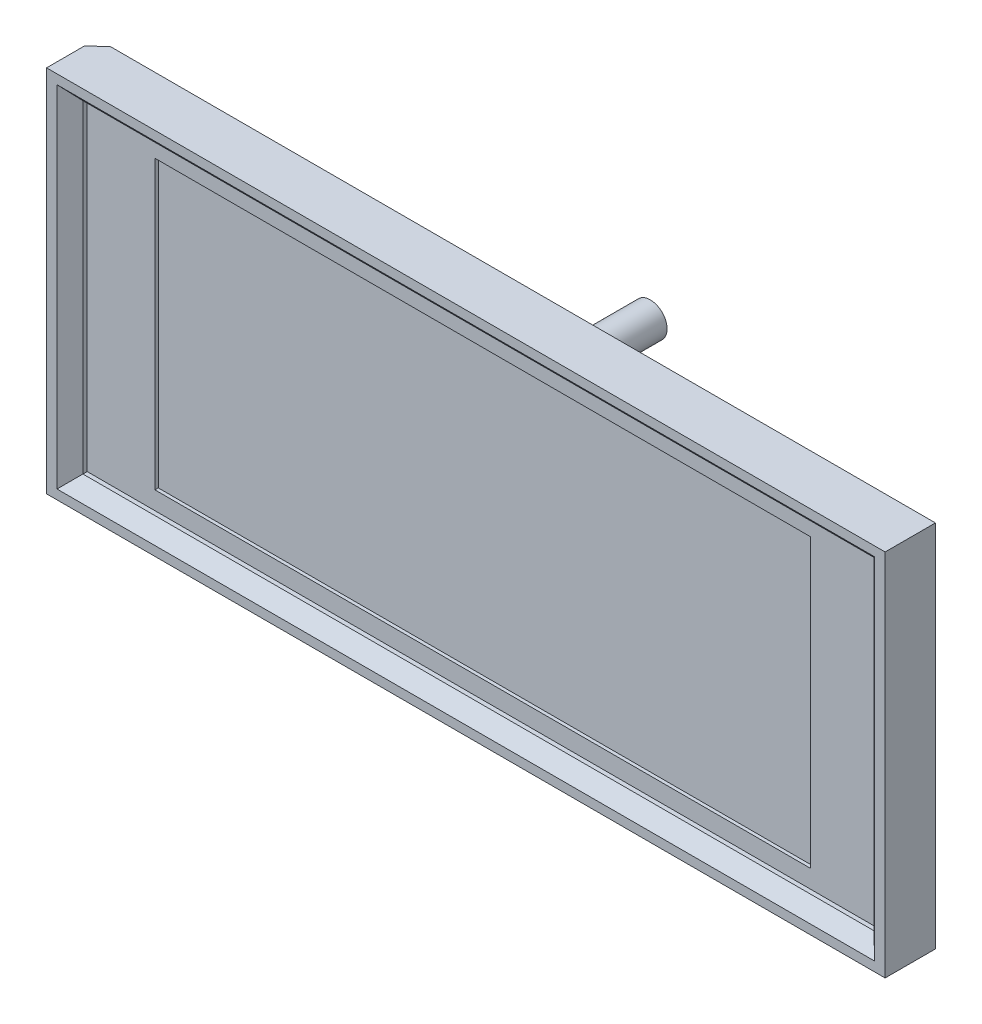
SolidWorks part; units mm, degrees
ref_plane "Front" through (0, 0, 0) normal (0, 0, 1) x (1, 0, 0)
ref_plane "Top" through (0, 0, 0) normal (0, 1, 0) x (1, 0, 0)
ref_plane "Right" through (0, 0, 0) normal (1, 0, 0) x (0, 0, -1)
sketch "草图2" plane through (0, 0, 0) normal (0, 0, 1) x (1, 0, 0)
  line L1 (-125, -55) -> (125, -55)
  line L2 (-125, -55) -> (-125, 55)
  line L3 (-125, 55) -> (125, 55)
  line L4 (125, -55) -> (125, 55)
  line L5 (-125, -55) -> (125, 55) construction
  line L6 (-125, 55) -> (125, -55) construction
  point P0 (0, 0)
extrude "凸台-拉伸1" add sketch "草图2" along normal blind 15
sketch "草图3" plane through (0, 0, 15) normal (0, 0, 1) x (1, 0, 0)
  line L1 (-117.8972, -48.1943) -> (117.8972, -48.1943)
  line L2 (-117.8972, -48.1943) -> (-117.8972, 48.1943)
  line L3 (-117.8972, 48.1943) -> (117.8972, 48.1943)
  line L4 (117.8972, -48.1943) -> (117.8972, 48.1943)
  line L5 (-117.8972, -48.1943) -> (117.8972, 48.1943) construction
  line L6 (-117.8972, 48.1943) -> (117.8972, -48.1943) construction
  point P0 (0, 0)
extrude "切除-拉伸1" cut sketch "草图3" against normal blind 5
sketch "草图4" plane through (0, 0, 10) normal (0, 0, 1) x (1, 0, 0)
  line L1 (-97.6929, -42.8107) -> (97.6929, -42.8107)
  line L2 (-97.6929, -42.8107) -> (-97.6929, 42.8107)
  line L3 (-97.6929, 42.8107) -> (97.6929, 42.8107)
  line L4 (97.6929, -42.8107) -> (97.6929, 42.8107)
  line L5 (-97.6929, -42.8107) -> (97.6929, 42.8107) construction
  line L6 (-97.6929, 42.8107) -> (97.6929, -42.8107) construction
  point P0 (0, 0)
extrude "切除-拉伸2" cut sketch "草图4" against normal blind 1
chamfer "倒角1" distance 4 angle 43 5 edges at (-125, 0, 0) (0, -48.1943, 15) (117.8972, 0, 15) (0, 48.1943, 15) (-117.8972, 0, 15)
sketch "草图6" plane through (0, 0, 0) normal (0, 0, -1) x (-1, 0, 0)
  circle A0 centre (0, 25.0933) radius 5
extrude "凸台-拉伸2" add sketch "草图6" along normal blind 40
